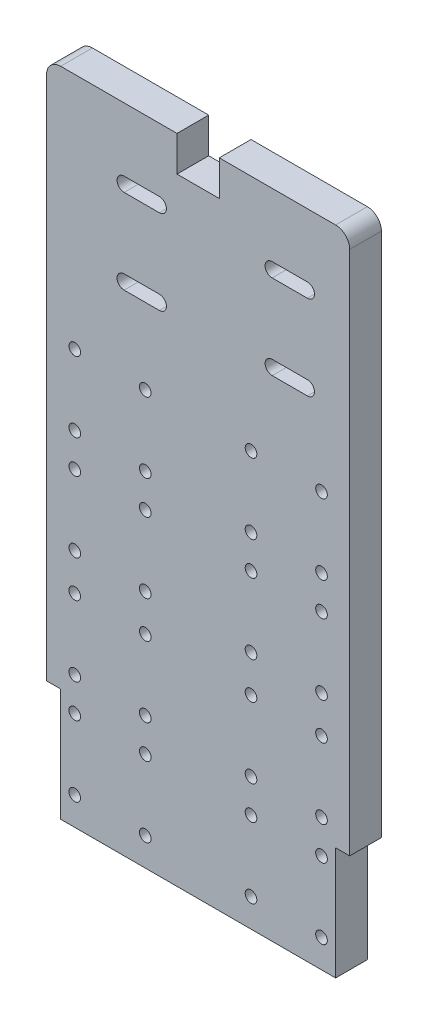
SolidWorks part; units mm, degrees
ref_plane "Front" through (0, 0, 0) normal (0, 0, 1) x (1, 0, 0)
ref_plane "Top" through (0, 0, 0) normal (0, 1, 0) x (1, 0, 0)
ref_plane "Right" through (0, 0, 0) normal (1, 0, 0) x (0, 0, -1)
sketch "Esquisse1" plane through (0, 0, 0) normal (0, 0, 1) x (1, 0, 0)
  line L1 (0, 0) -> (86, 0)
  line L2 (0, 0) -> (0, 185)
  line L3 (0, 185) -> (86, 185)
  line L4 (86, 0) -> (86, 185)
  dimension "D1" = 86
  dimension "D2" = 185
extrude "Boss.-Extru.1" add sketch "Esquisse1" along normal blind 9
sketch "Esquisse2" plane through (0, 0, 9) normal (0, 0, 1) x (1, 0, 0)
  line L0 (0, 47.5) -> (86, 47.5) construction
  line L1 (0, 185) -> (0, 0) construction
  line L2 (86, 0) -> (86, 185) construction
  line L3 (43, 47.5) -> (43, 77.5) construction
  line L4 (18, 47.5) -> (18, 38.434) construction
  line L5 (43, 77.5) -> (6.8221, 77.5) construction
  line L6 (18, 107.5) -> (18, 116.566) construction
  line L7 (0, 107.5) -> (86, 107.5) construction
  line L8 (0, 0) -> (86, 0) construction
  circle A0 centre (8, 57.5) radius 1.65
  circle A1 centre (28, 57.5) radius 1.65
  circle A2 centre (28, 37.5) radius 1.65
  circle A3 centre (8, 37.5) radius 1.65
  circle A4 centre (78, 37.5) radius 1.65
  circle A5 centre (58, 37.5) radius 1.65
  circle A6 centre (58, 57.5) radius 1.65
  circle A7 centre (78, 57.5) radius 1.65
  circle A8 centre (78, 97.5) radius 1.65
  circle A9 centre (58, 97.5) radius 1.65
  circle A10 centre (58, 117.5) radius 1.65
  circle A11 centre (78, 117.5) radius 1.65
  circle A12 centre (8, 117.5) radius 1.65
  circle A13 centre (28, 117.5) radius 1.65
  circle A14 centre (28, 97.5) radius 1.65
  circle A15 centre (8, 97.5) radius 1.65
  dimension "D1" = 20
  dimension "D2" = 20
  dimension "D3" = 3.3
  dimension "D4" = 25
  dimension "D5" = 40
  dimension "D6" = 47.5
extrude "Enlèv. mat.-Extru.1" cut sketch "Esquisse2" against normal through all
sketch "Esquisse3" plane through (0, 0, 9) normal (0, 0, 1) x (1, 0, 0)
  line L0 (43, 0) -> (43, 185) construction
  line L1 (0, 0) -> (86, 0) construction
  line L2 (86, 185) -> (0, 185) construction
  line L3 (43, 18) -> (1.3662, 18) construction
  line L4 (18, 18) -> (18, 55.2921) construction
  line L5 (43, 48) -> (3.2443, 48) construction
  line L6 (18, 78) -> (18, 40.7079) construction
  line L7 (68, 78) -> (68, 40.7079) construction
  line L8 (68, 18) -> (68, 55.2921) construction
  circle A0 centre (8, 28) radius 1.65
  circle A1 centre (8, 8) radius 1.65
  circle A2 centre (28, 8) radius 1.65
  circle A3 centre (28, 28) radius 1.65
  circle A4 centre (28, 68) radius 1.65
  circle A5 centre (28, 88) radius 1.65
  circle A6 centre (8, 88) radius 1.65
  circle A7 centre (8, 68) radius 1.65
  circle A8 centre (78, 68) radius 1.65
  circle A9 centre (78, 88) radius 1.65
  circle A10 centre (58, 88) radius 1.65
  circle A11 centre (58, 68) radius 1.65
  circle A12 centre (58, 28) radius 1.65
  circle A13 centre (58, 8) radius 1.65
  circle A14 centre (78, 8) radius 1.65
  circle A15 centre (78, 28) radius 1.65
  dimension "D1" = 20
  dimension "D6" = 3.3
  dimension "D2" = 20
  dimension "D3" = 25
  dimension "D4" = 60
  dimension "D5" = 18
extrude "Enlèv. mat.-Extru.2" cut sketch "Esquisse3" against normal through all
sketch "Esquisse4" plane through (0, 0, 9) normal (0, 0, 1) x (1, 0, 0)
  line L0 (43, 0) -> (43, 48.0891) construction
  line L1 (0, 0) -> (4, 0)
  line L2 (0, 0) -> (0, 32)
  line L3 (0, 32) -> (4, 32)
  line L4 (4, 0) -> (4, 32)
  line L5 (0, 0) -> (86, 0) construction
  line L6 (82, 0) -> (82, 32)
  line L7 (86, 32) -> (82, 32)
  line L8 (86, 0) -> (86, 32)
  line L9 (86, 0) -> (82, 0)
  dimension "D1" = 4
  dimension "D2" = 32
extrude "Enlèv. mat.-Extru.3" cut sketch "Esquisse4" against normal through all
sketch "Esquisse6" plane through (0, 0, 9) normal (0, 0, 1) x (1, 0, 0)
  line L0 (22, 165) -> (32, 165) construction
  line L1 (22, 167) -> (32, 167)
  line L2 (22, 163) -> (32, 163)
  line L3 (27, 165) -> (27, 153) construction
  line L4 (27, 153) -> (48, 153) construction
  line L5 (22, 141) -> (32, 141) construction
  line L6 (22, 139) -> (32, 139)
  line L7 (22, 143) -> (32, 143)
  line L8 (48, 153) -> (48, 155.9774) construction
  line L9 (74, 165) -> (64, 165) construction
  line L10 (74, 167) -> (64, 167)
  line L11 (74, 163) -> (64, 163)
  line L12 (74, 141) -> (64, 141) construction
  line L13 (74, 139) -> (64, 139)
  line L14 (74, 143) -> (64, 143)
  line L15 (0, 185) -> (0, 32) construction
  arc A0 (22, 167) -> (22, 163) centre (22, 165) ccw
  arc A1 (32, 163) -> (32, 167) centre (32, 165) ccw
  arc A2 (22, 139) -> (22, 143) centre (22, 141) cw
  arc A3 (32, 143) -> (32, 139) centre (32, 141) cw
  arc A4 (74, 167) -> (74, 163) centre (74, 165) cw
  arc A5 (64, 163) -> (64, 167) centre (64, 165) cw
  arc A6 (74, 139) -> (74, 143) centre (74, 141) ccw
  arc A7 (64, 143) -> (64, 139) centre (64, 141) ccw
  circle A8 centre (28, 117.5) radius 1.65 construction
  point P2 (27, 165)
  point P12 (27, 141)
  point P22 (69, 165)
  point P29 (69, 141)
  dimension "D1" = 4
  dimension "D2" = 10
  dimension "D3" = 42
  dimension "D4" = 24
  dimension "D5" = 35.5
  dimension "D6" = 22
extrude "Enlèv. mat.-Extru.4" cut sketch "Esquisse6" against normal through all
sketch "Esquisse7" plane through (0, 0, 9) normal (0, 0, 1) x (1, 0, 0)
  line L0 (43, 185) -> (43, 175) construction
  line L1 (86, 185) -> (0, 185) construction
  line L2 (49, 175) -> (37, 175)
  line L3 (37, 175) -> (37, 185)
  line L4 (37, 185) -> (49, 185)
  line L5 (49, 175) -> (49, 185)
  dimension "D1" = 12
  dimension "D2" = 10
extrude "Enlèv. mat.-Extru.5" cut sketch "Esquisse7" against normal through all
fillet "Congé1" radius 4 2 edges at (86, 185, 4.5) (0, 185, 4.5)
